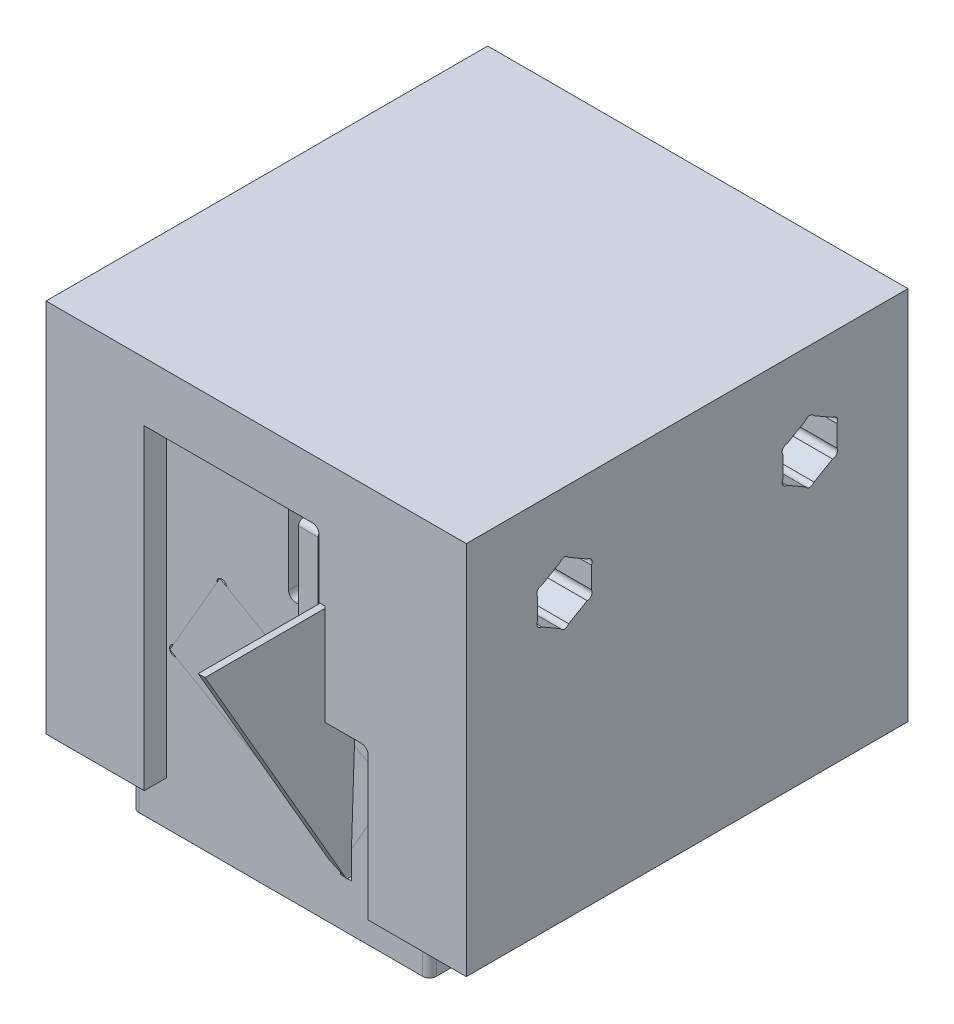
SolidWorks part; units mm, degrees
other "Cutter extra large H-shaped blade"
other "aluminum plate"
other "Rubber sheet 60° shore"
ref_plane "Front Plane" through (0, 0, 0) normal (0, 0, 1) x (1, 0, 0)
ref_plane "Top Plane" through (0, 0, 0) normal (0, 1, 0) x (1, 0, 0)
ref_plane "Right Plane" through (0, 0, 0) normal (1, 0, 0) x (0, 0, -1)
sketch "ｽｹｯﾁ1" plane through (0, 0, 0) normal (0, 0, 1) x (1, 0, 0)
  line L0 (-11.1603, 0.6699) -> (6.1603, -9.3301)
  line L1 (-11.1603, 0.6699) -> (-6.1603, 9.3301)
  line L2 (6.1603, -9.3301) -> (11.1603, -0.6699)
  line L3 (-6.1603, 9.3301) -> (11.1603, -0.6699)
  line L4 (-11.1603, 0.6699) -> (11.1603, -0.6699) construction
  line L5 (6.1603, -9.3301) -> (-6.1603, 9.3301) construction
  line L6 (0, 0) -> (19.0735, 0) construction
  line L7 (6.6603, 26.7667) -> (6.6603, -11.3835) construction
  line L8 (53.9947, 4.7554) -> (63.9947, 4.7554)
  line L9 (63.9947, 4.7554) -> (58.9947, 14.7554)
  line L10 (58.9947, 14.7554) -> (53.9947, 14.7554)
  line L11 (53.9947, 14.7554) -> (53.9947, 4.7554) construction
  line L12 (-2.5, -4.3301) -> (5.5125, 9.5479) construction
  line L14 (15.1603, 21.3301) -> (-15.1603, 21.3301)
  line L15 (15.1603, 21.3301) -> (15.1603, -15.3301)
  line L16 (15.1603, -15.3301) -> (-15.1603, -15.3301)
  line L17 (-15.1603, 21.3301) -> (-15.1603, -15.3301)
  line L18 (7.0103, 14.6699) -> (6.3103, 14.6699)
  line L19 (7.0103, 14.6699) -> (7.0103, -10.3301)
  line L20 (7.0103, -10.3301) -> (6.3103, -10.3301)
  line L21 (6.3103, 14.6699) -> (6.3103, -10.3301)
  point P1 (0, 0)
  point P16 (0, 0)
  point P23 (6.3103, 2.1303)
  dimension "D1" = 10
  dimension "D2" = 20
  dimension "D3" = 30
  dimension "D4" = 0.5
  dimension "D5" = 20
  dimension "D6" = 10
  dimension "D7" = 10
  dimension "D8" = 63.435
  dimension "D9" = 0.7
  dimension "D10" = 25
  dimension "D11" = 1
  dimension "D12" = 12.5396
  dimension "D13" = 12
  dimension "D14" = 4
  dimension "D15" = 4
  dimension "D16" = 6
  dimension "D17" = 8.7994
sketch "ｽｹｯﾁ2" plane through (0, 0, 0) normal (0, 0, 1) x (1, 0, 0)
  line L3 (7.5103, 4.3667) -> (7.5103, 1.5529)
  line L20 (15.1603, 21.3301) -> (-15.1603, 21.3301)
  line L21 (-15.1603, 21.3301) -> (-15.1603, -15.3301)
  line L22 (-15.1603, -15.3301) -> (15.1603, -15.3301)
  line L23 (15.1603, -15.3301) -> (15.1603, 21.3301)
  line L24 (0.8031, 21.3301) -> (-15.1603, 21.3301)
  line L25 (-15.1603, 21.3301) -> (-15.1603, -15.3301)
  line L26 (-15.1603, -15.3301) -> (15.1603, -15.3301)
  line L27 (15.1603, -15.3301) -> (15.1603, 4.3667)
  line L29 (7.0103, 14.6699) -> (7.0103, -10.3301) construction
  line L31 (3.8031, 11.1988) -> (3.8031, 3.6932)
  line L32 (15.1603, 4.3667) -> (7.5103, 4.3667)
  line L35 (-6.1969, 9.4667) -> (-11.2969, 0.6333)
  line L36 (-11.2969, 0.6333) -> (6.1969, -9.4667)
  line L37 (11.2969, -0.6333) -> (-6.1969, 9.4667)
  line L38 (6.1969, -9.4667) -> (11.2969, -0.6333)
  line L39 (-6.1969, 9.4667) -> (-11.2969, 0.6333)
  line L40 (-11.2969, 0.6333) -> (6.1103, -9.4167)
  line L41 (11.2969, -0.6333) -> (7.5103, 1.5529)
  line L42 (7.2103, -7.7115) -> (11.2969, -0.6333)
  line L45 (3.8031, 3.6932) -> (-6.1969, 9.4667)
  line L49 (7.2103, 14.8699) -> (6.1103, 14.8699)
  line L50 (6.1103, 14.8699) -> (6.1103, -10.5301)
  line L51 (6.1103, -10.5301) -> (7.2103, -10.5301)
  line L52 (7.2103, -10.5301) -> (7.2103, 14.8699)
  line L54 (6.1103, -9.4167) -> (6.1103, -10.5301)
  line L55 (6.1103, -10.5301) -> (7.2103, -10.5301)
  line L56 (7.2103, -10.5301) -> (7.2103, -7.7115)
  line L57 (3.8031, 11.1988) -> (0.8031, 11.1988)
  line L58 (0.8031, 21.3301) -> (0.8031, 11.1988)
  point P17 (2.3031, 15.2645)
  dimension "D1" = 0.1
  dimension "D2" = 10
  dimension "D4" = 5
  dimension "D5" = 0.2
  dimension "D6" = 0.5
  dimension "D7" = 3
  dimension "D8" = 5
  dimension "D3" = 0
extrude "ﾎﾞｽ - 押し出し1" add sketch "ｽｹｯﾁ2" along normal mid plane 40
sketch "ｽｹｯﾁ3" plane through (0, 0, 0) normal (0, 0, 1) x (1, 0, 0)
  line L0 (21.4103, -10.6333) -> (15.4103, -10.6333)
  line L1 (15.1603, 4.3667) -> (7.5103, 4.3667) construction
  line L14 (21.4103, -10.6333) -> (21.4103, 27.5801)
  line L15 (-21.4103, -10.6333) -> (-21.4103, 27.5801)
  line L16 (-21.4103, 27.5801) -> (21.4103, 27.5801)
  line L17 (-15.4103, -10.6333) -> (-21.4103, -10.6333)
  line L18 (15.4103, 21.5801) -> (-15.4103, 21.5801)
  line L19 (-15.4103, 21.5801) -> (-15.4103, -15.5801)
  line L20 (-15.4103, -15.5801) -> (15.4103, -15.5801)
  line L21 (15.4103, -15.5801) -> (15.4103, 21.5801)
  line L22 (6.4103, 21.5801) -> (-15.4103, 21.5801)
  line L23 (-15.4103, 21.5801) -> (-15.4103, -10.6333)
  line L25 (15.4103, -10.6333) -> (15.4103, 4.6167)
  line L26 (15.4103, 4.6167) -> (7.0103, 4.6167)
  line L27 (7.0103, 14.6699) -> (7.0103, -10.3301) construction
  line L28 (7.0103, 4.6167) -> (7.0103, 14.8699)
  line L29 (7.0103, 14.8699) -> (6.4103, 14.8699)
  line L30 (6.4103, 14.8699) -> (6.4103, 21.5801)
  line L32 (7.0103, 14.6699) -> (6.3103, 14.6699) construction
  line L33 (6.4103, 18.225) -> (22.8856, 18.225) construction
  line L34 (6.3103, 14.6699) -> (6.3103, -10.3301) construction
  dimension "D1" = 15
  dimension "D3" = 6
  dimension "D4" = 6
  dimension "D5" = 6
  dimension "D6" = 0.2
  dimension "D7" = 0.25
  dimension "D8" = 0.1
  dimension "D2" = 0.25
extrude "ﾎﾞｽ - 押し出し2" add sketch "ｽｹｯﾁ3" along normal mid plane 45 separate body
sketch "ｽｹｯﾁ4" plane through (6.4103, 0, 0) normal (-1, 0, 0) x (0, 0, 1)
  line L0 (-22.5, 18.225) -> (22.5, 18.225) construction
  line L1 (-22.5, 21.5801) -> (-22.5, 14.8699) construction
  line L2 (22.5, 21.5801) -> (22.5, 14.8699) construction
  line L3 (0, 0) -> (0, 23.4248) construction
  line L4 (0, 26.7667) -> (0, -11.3835) construction
  circle A0 centre (-12.5, 18.225) radius 1.7
  circle A1 centre (12.5, 18.225) radius 1.7
  dimension "D1" = 3.4
  dimension "D2" = 10
extrude "ｶｯﾄ - 押し出し1" cut sketch "ｽｹｯﾁ4" against normal through all both and the other way through all
sketch "ｽｹｯﾁ5" plane through (-21.4103, 0, 0) normal (-1, 0, 0) x (0, 0, 1)
  circle A0 centre (-12.5, 18.225) radius 3
  circle A1 centre (12.5, 18.225) radius 3
  dimension "D1" = 6
extrude "ｶｯﾄ - 押し出し2" cut sketch "ｽｹｯﾁ5" against normal up to surface (6 mm away) up to face at (-15.4103, 16.525, -12.5)
ref_plane "平面1" through (6.3103, 0, 0) normal (1, 0, 0) x (0, 0, -1)
sketch "ｽｹｯﾁ7" plane through (6.3103, 0, 0) normal (1, 0, 0) x (0, 0, -1)
  line L0 (0, 0) -> (0, 18.4458) construction
  line L1 (22.5, 6.8699) -> (-22.5, 6.8699)
  line L2 (22.5, 6.8699) -> (22.5, 21.0801)
  line L3 (22.5, 21.0801) -> (-22.5, 21.0801)
  line L4 (-22.5, 6.8699) -> (-22.5, 21.0801)
  line L5 (22.5, 6.8699) -> (-22.5, 21.0801) construction
  line L6 (22.5, 21.0801) -> (-22.5, 6.8699) construction
  line L7 (0, 26.7667) -> (0, -11.3835) construction
  line L8 (-22.5, 21.5801) -> (22.5, 21.5801) construction
  line L10 (22.5, 21.5801) -> (22.5, 14.8699) construction
  line L11 (-22.5, 21.5801) -> (-22.5, 14.8699) construction
  line L12 (-22.5, 14.8699) -> (22.5, 14.8699) construction
  circle A0 centre (12.5, 18.225) radius 1.7 construction
  circle A1 centre (-12.5, 18.225) radius 1.7 construction
  circle A2 centre (-12.5, 18.225) radius 1.7
  circle A3 centre (12.5, 18.225) radius 1.7
  point P4 (0, 13.975)
  dimension "D1" = 0.5
  dimension "D2" = 8
extrude "ﾎﾞｽ - 押し出し3" add sketch "ｽｹｯﾁ7" against normal blind 2 separate body
sketch "ｽｹｯﾁ8" plane through (0, -10.6333, 0) normal (0, -1, 0) x (1, 0, 0)
  line L0 (29.2941, 0) -> (0, 0) construction
  line L1 (0, 0) -> (0, 30.6255) construction
  line L2 (-15.1603, 20) -> (15.1603, 20) construction
  line L3 (15.4103, 22.5) -> (11.4103, 22.5)
  line L4 (15.4103, 22.5) -> (15.4103, 20.25)
  line L5 (15.4103, 20.25) -> (11.4103, 20.25)
  line L6 (11.4103, 22.5) -> (11.4103, 20.25)
  line L7 (15.4103, 22.5) -> (11.4103, 20.25) construction
  line L8 (15.4103, 20.25) -> (11.4103, 22.5) construction
  line L9 (-15.4103, 20.25) -> (-11.4103, 22.5) construction
  line L10 (-15.4103, 22.5) -> (-11.4103, 20.25) construction
  line L11 (-11.4103, 22.5) -> (-11.4103, 20.25)
  line L12 (-15.4103, 20.25) -> (-11.4103, 20.25)
  line L13 (-15.4103, 22.5) -> (-15.4103, 20.25)
  line L14 (-15.4103, 22.5) -> (-11.4103, 22.5)
  line L15 (-15.4103, -22.5) -> (-11.4103, -20.25) construction
  line L16 (-15.4103, -20.25) -> (-11.4103, -22.5) construction
  line L17 (15.4103, -20.25) -> (11.4103, -22.5) construction
  line L18 (15.4103, -22.5) -> (11.4103, -20.25) construction
  line L19 (-15.4103, -22.5) -> (-11.4103, -22.5)
  line L20 (-15.4103, -22.5) -> (-15.4103, -20.25)
  line L21 (-15.4103, -20.25) -> (-11.4103, -20.25)
  line L22 (-11.4103, -22.5) -> (-11.4103, -20.25)
  line L23 (11.4103, -22.5) -> (11.4103, -20.25)
  line L24 (15.4103, -20.25) -> (11.4103, -20.25)
  line L25 (15.4103, -22.5) -> (15.4103, -20.25)
  line L26 (15.4103, -22.5) -> (11.4103, -22.5)
  point P8 (13.4103, 21.375)
  point P16 (-13.4103, 21.375)
  point P25 (-13.4103, -21.375)
  point P26 (13.4103, -21.375)
  dimension "D1" = 0.25
  dimension "D2" = 4
extrude "ﾎﾞｽ - 押し出し4" add sketch "ｽｹｯﾁ8" against normal up to surface (32.2134 mm away) up to face at (-4.5, 21.5801, 0)
sketch "ｽｹｯﾁ9" plane through (21.4103, 0, 0) normal (1, 0, 0) x (0, 0, -1)
  line L0 (0, 0) -> (0, 19.5285) construction
  line L1 (-12.933, 21.1504) -> (-14.817, 20.0627)
  line L2 (-15.25, 19.3127) -> (-15.25, 17.1373)
  line L3 (-14.817, 16.3873) -> (-12.933, 15.2996)
  line L4 (-12.067, 15.2996) -> (-10.183, 16.3873)
  line L5 (-9.75, 17.1373) -> (-9.75, 19.3127)
  line L6 (-10.183, 20.0627) -> (-12.067, 21.1504)
  line L7 (0, 26.7667) -> (0, -11.3835) construction
  line L8 (-12.5, 21.4004) -> (-12.5, 18.225) construction
  line L9 (12.5, 21.4004) -> (12.5, 18.225) construction
  line L10 (10.183, 20.0627) -> (12.067, 21.1504)
  line L11 (9.75, 17.1373) -> (9.75, 19.3127)
  line L12 (12.067, 15.2996) -> (10.183, 16.3873)
  line L13 (14.817, 16.3873) -> (12.933, 15.2996)
  line L14 (15.25, 19.3127) -> (15.25, 17.1373)
  line L15 (12.933, 21.1504) -> (14.817, 20.0627)
  circle A0 centre (-12.5, 18.225) radius 2.75 construction
  arc A1 (-12.067, 21.1504) -> (-12.933, 21.1504) centre (-12.5, 20.9004) ccw
  arc A2 (-9.75, 19.3127) -> (-10.183, 20.0627) centre (-10.183, 19.5627) ccw
  arc A3 (-10.183, 16.3873) -> (-9.75, 17.1373) centre (-10.183, 16.8873) ccw
  arc A4 (-12.933, 15.2996) -> (-12.067, 15.2996) centre (-12.5, 15.5496) ccw
  arc A5 (-15.25, 17.1373) -> (-14.817, 16.3873) centre (-14.817, 16.8873) ccw
  arc A6 (-14.817, 20.0627) -> (-15.25, 19.3127) centre (-14.817, 19.5627) ccw
  circle A7 centre (12.5, 18.225) radius 2.75 construction
  arc A8 (14.817, 20.0627) -> (15.25, 19.3127) centre (14.817, 19.5627) cw
  arc A9 (15.25, 17.1373) -> (14.817, 16.3873) centre (14.817, 16.8873) cw
  arc A10 (12.933, 15.2996) -> (12.067, 15.2996) centre (12.5, 15.5496) cw
  arc A11 (10.183, 16.3873) -> (9.75, 17.1373) centre (10.183, 16.8873) cw
  arc A12 (9.75, 19.3127) -> (10.183, 20.0627) centre (10.183, 19.5627) cw
  arc A13 (12.067, 21.1504) -> (12.933, 21.1504) centre (12.5, 20.9004) cw
  point P35 (-12.5, 18.225)
  dimension "D2" = 1
  dimension "D3" = 6
  dimension "D1" = 5.5
extrude "ｶｯﾄ - 押し出し3" cut sketch "ｽｹｯﾁ9" against normal blind 5
sketch "ｽｹｯﾁ10" plane through (0, 0, 20) normal (0, 0, 1) x (1, 0, 0)
  line L0 (-10.8139, 0.7627) -> (-11.2969, 0.6333) construction
  line L1 (6.1103, -9.4167) -> (-11.2969, 0.6333) construction
  circle A0 centre (10.7975, -0.6578) radius 0.5
  circle A1 centre (-6.0071, 9.0041) radius 0.5
  circle A2 centre (-10.8139, 0.7627) radius 0.5
  dimension "D1" = 45
  dimension "D3" = 1
extrude "ｶｯﾄ - 押し出し4" cut sketch "ｽｹｯﾁ10" against normal through all
fillet "ﾌｨﾚｯﾄ1" radius 0.7 12 edges at (15.1603, -5.4817, 20) (15.1603, 4.3667, 0) (11.3353, 4.3667, -20) (11.3353, 4.3667, 20) (3.8031, 3.6932, 0) (-7.1786, 21.3301, 20) (-7.1786, 21.3301, -20) (-15.1603, 3, 20) (-15.1603, 21.3301, 0) (-15.1603, 3, -20) (15.1603, -5.4817, -20) (0.8031, 11.1988, 0)
fillet "ﾌｨﾚｯﾄ2" radius 0.7 12 edges at (6.4103, 21.5801, 0) (-15.4103, 5.4734, 20.25) (-13.4103, 21.5801, 20.25) (-15.4103, 5.4734, -20.25) (-13.4103, 21.5801, -20.25) (-15.4103, 21.5801, 0) (13.4103, 4.6167, -20.25) (15.4103, -3.0083, -20.25) (11.4103, 4.6167, 21.375) (13.4103, 4.6167, 20.25) (15.4103, 4.6167, 0) (15.4103, -3.0083, 20.25)
fillet "ﾌｨﾚｯﾄ3" radius 0.5 4 edges at (5.3103, 21.0801, 22.5) (5.3103, 6.8699, 22.5) (5.3103, 6.8699, -22.5) (5.3103, 21.0801, -22.5)
sketch "ｽｹｯﾁ11" plane through (7.0103, 0, 0) normal (-1, 0, 0) x (0, 0, 1)
  line L0 (-7.2813, 14.6699) -> (-21.715, -10.3301)
  line L1 (-21.715, -10.3301) -> (20.285, -10.3301)
  line L2 (20.285, -10.3301) -> (34.7187, 14.6699)
  line L3 (34.7187, 14.6699) -> (-7.2813, 14.6699)
  dimension "D1" = 25
  dimension "D2" = 42
  dimension "D3" = 60
extrude "ﾎﾞｽ - 押し出し5" add sketch "ｽｹｯﾁ11" along normal blind 0.7 separate body
sketch "ｽｹｯﾁ12" plane through (4.3103, 0, 0) normal (-1, 0, 0) x (0, 0, 1)
  line L0 (-22.5, 21.5801) -> (22.5, 21.5801) construction
  circle A0 centre (-12.5, 18.225) radius 3.3551
sketch "ｽｹｯﾁ13" plane through (0, 0, -22.5) normal (0, 0, -1) x (-1, 0, 0)
  line L0 (-7.0103, -10.3301) -> (-6.3103, -8.3078)
  line L1 (-6.3103, 13.75) -> (-6.3103, -13.75) construction
  line L2 (-6.3103, -8.3078) -> (-6.3103, -10.3301)
  line L3 (-6.3103, -10.3301) -> (-7.0103, -10.3301) construction
  line L4 (-6.3103, -10.3301) -> (-7.0103, -10.3301)
extrude "ｶｯﾄ - 押し出し5" cut sketch "ｽｹｯﾁ13" against normal through all
sketch "ｽｹｯﾁ14" plane through (0, 0, 20) normal (0, 0, 1) x (1, 0, 0)
  line L0 (-11.2969, 0.6333) -> (6.1103, -9.4167)
  line L1 (-11.2969, 0.6333) -> (-6.1969, 9.4667)
  line L2 (6.1103, -9.4167) -> (6.3103, -9.0703)
  line L3 (-6.1969, 9.4667) -> (6.3103, 2.2457)
  line L4 (6.1103, -9.4167) -> (-10.6845, 0.2797) construction
  line L5 (-10.9433, 1.2456) -> (-6.5026, 8.9372) construction
  line L7 (6.3103, 2.2457) -> (6.3103, -9.0703)
  line L8 (6.3103, -13.75) -> (6.3103, 13.75) construction
  line L9 (7.5103, 1.5529) -> (7.2103, -7.7115)
  line L10 (7.2103, -7.7115) -> (11.2969, -0.6333)
  line L11 (11.2969, -0.6333) -> (7.5103, 1.5529)
  line L12 (7.5103, 1.5529) -> (10.569, -0.213) construction
extrude "ﾎﾞｽ - 押し出し6" add sketch "ｽｹｯﾁ14" against normal up to surface (40 mm away) separate body up to face at (1.9549, 1.962, -20)
sketch "ｽｹｯﾁ15" plane through (0, 27.5801, 0) normal (0, 1, 0) x (1, 0, 0)
  text T0 "PUSH\r\nAND\r\nCUT" font "Century Gothic" height in points 24
